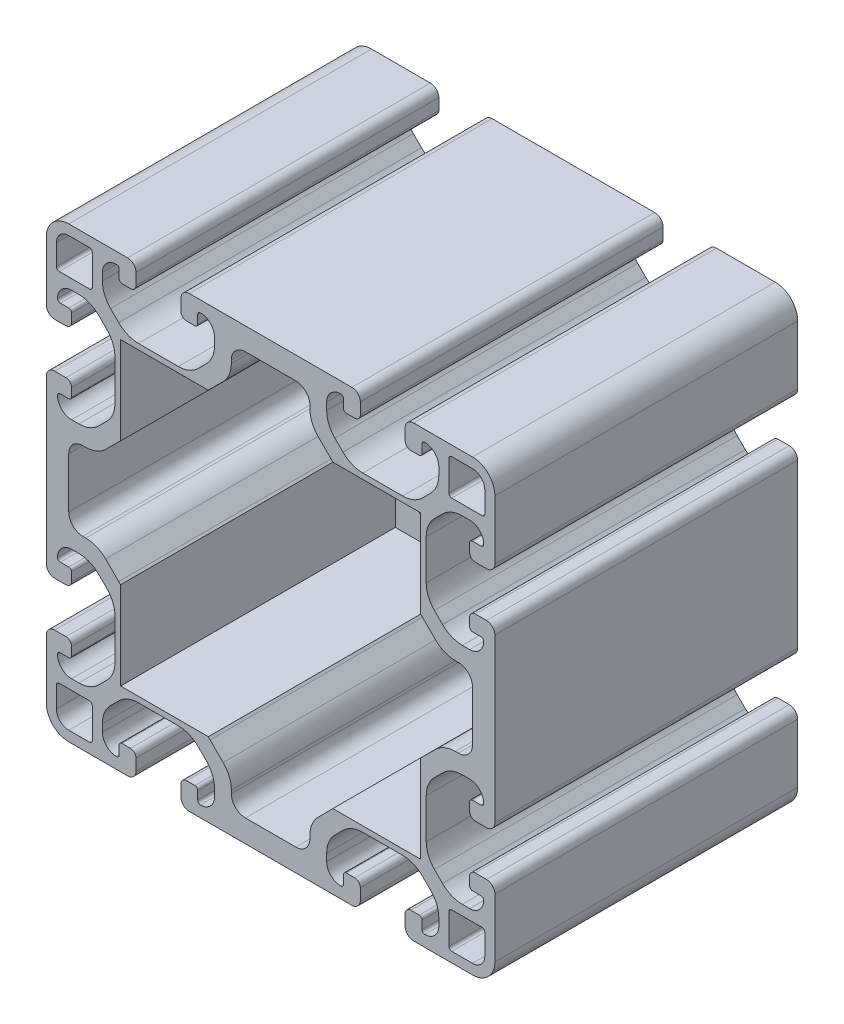
SolidWorks part; units mm, degrees
ref_plane "Plan de face" through (0, 0, 0) normal (0, 0, 1) x (1, 0, 0)
ref_plane "Plan de dessus" through (0, 0, 0) normal (0, 1, 0) x (1, 0, 0)
ref_plane "Plan de droite" through (0, 0, 0) normal (1, 0, 0) x (0, 0, -1)
ref_plane "Plan1" through (0, 0, -30) normal (0, 0, -1) x (-1, 0, 0)
sketch "Esquisse1" plane through (0, 0, -30) normal (0, 0, -1) x (-1, 0, 0)
  line L0 (-4.5, 55) -> (-4.5, 53.5)
  line L1 (-4, 53) -> (-2.5, 53)
  line L2 (-4.5, 50) -> (-5.8076, 50)
  line L3 (-9.3431, 51.4645) -> (-10.7855, 52.9069)
  line L4 (-12.25, 56.4424) -> (-12.25, 63.5576)
  line L5 (-10.7855, 67.0931) -> (-9.3431, 68.5355)
  line L6 (-5.8076, 70) -> (-4.5, 70)
  line L7 (-2.5, 67) -> (-4, 67)
  line L8 (-4.5, 66.5) -> (-4.5, 65)
  line L9 (-3.5, 64) -> (-1.5, 64)
  line L10 (0, 65.5) -> (0, 76)
  line L11 (-4, 80) -> (-14.5, 80)
  line L12 (-16, 78.5) -> (-16, 76.5)
  line L13 (-15, 75.5) -> (-13.5, 75.5)
  line L14 (-13, 76) -> (-13, 77.5)
  line L15 (-10, 75.5) -> (-10, 74.1924)
  line L16 (-11.4645, 70.6569) -> (-12.9069, 69.2145)
  line L17 (-16.4424, 67.75) -> (-23.5576, 67.75)
  line L18 (-27.0931, 69.2145) -> (-28.5355, 70.6569)
  line L19 (-30, 74.1924) -> (-30, 75.5)
  line L20 (-27, 77.5) -> (-27, 76)
  line L21 (-26.5, 75.5) -> (-25, 75.5)
  line L22 (-24, 76.5) -> (-24, 78.5)
  line L23 (-25.5, 80) -> (-54.5, 80)
  line L24 (-56, 78.5) -> (-56, 76.5)
  line L25 (-55, 75.5) -> (-53.5, 75.5)
  line L26 (-53, 76) -> (-53, 77.5)
  line L27 (-50, 75.5) -> (-50, 74.1924)
  line L28 (-51.4645, 70.6569) -> (-52.9069, 69.2145)
  line L29 (-56.4424, 67.75) -> (-63.5576, 67.75)
  line L30 (-67.0931, 69.2145) -> (-68.5355, 70.6569)
  line L31 (-70, 74.1924) -> (-70, 75.5)
  line L32 (-67, 77.5) -> (-67, 76)
  line L33 (-66.5, 75.5) -> (-65, 75.5)
  line L34 (-64, 76.5) -> (-64, 78.5)
  line L35 (-65.5, 80) -> (-76, 80)
  line L36 (-80, 76) -> (-80, 65.5)
  line L37 (-78.5, 64) -> (-76.5, 64)
  line L38 (-75.5, 65) -> (-75.5, 66.5)
  line L39 (-76, 67) -> (-77.5, 67)
  line L40 (-75.5, 70) -> (-74.1924, 70)
  line L41 (-70.6569, 68.5355) -> (-69.2145, 67.0931)
  line L42 (-67.75, 63.5576) -> (-67.75, 56.4424)
  line L43 (-69.2145, 52.9069) -> (-70.6569, 51.4645)
  line L44 (-74.1924, 50) -> (-75.5, 50)
  line L45 (-77.5, 53) -> (-76, 53)
  line L46 (-75.5, 53.5) -> (-75.5, 55)
  line L47 (-76.5, 56) -> (-78.5, 56)
  line L48 (-80, 54.5) -> (-80, 25.5)
  line L49 (-78.5, 24) -> (-76.5, 24)
  line L50 (-75.5, 25) -> (-75.5, 26.5)
  line L51 (-76, 27) -> (-77.5, 27)
  line L52 (-75.5, 30) -> (-74.1924, 30)
  line L53 (-70.6569, 28.5355) -> (-69.2145, 27.0931)
  line L54 (-67.75, 23.5576) -> (-67.75, 16.4424)
  line L55 (-69.2145, 12.9069) -> (-70.6569, 11.4645)
  line L56 (-74.1924, 10) -> (-75.5, 10)
  line L57 (-77.5, 13) -> (-76, 13)
  line L58 (-75.5, 13.5) -> (-75.5, 15)
  line L59 (-76.5, 16) -> (-78.5, 16)
  line L60 (-80, 14.5) -> (-80, 4)
  line L61 (-76, 0) -> (-65.5, 0)
  line L62 (-64, 1.5) -> (-64, 3.5)
  line L63 (-65, 4.5) -> (-66.5, 4.5)
  line L64 (-67, 4) -> (-67, 2.5)
  line L65 (-70, 4.5) -> (-70, 5.8076)
  line L66 (-68.5355, 9.3431) -> (-67.0931, 10.7855)
  line L67 (-63.5576, 12.25) -> (-56.4424, 12.25)
  line L68 (-52.9069, 10.7855) -> (-51.4645, 9.3431)
  line L69 (-50, 5.8076) -> (-50, 4.5)
  line L70 (-53, 2.5) -> (-53, 4)
  line L71 (-53.5, 4.5) -> (-55, 4.5)
  line L72 (-56, 3.5) -> (-56, 1.5)
  line L73 (-54.5, 0) -> (-25.5, 0)
  line L74 (-24, 1.5) -> (-24, 3.5)
  line L75 (-25, 4.5) -> (-26.5, 4.5)
  line L76 (-27, 4) -> (-27, 2.5)
  line L77 (-30, 4.5) -> (-30, 5.8076)
  line L78 (-28.5355, 9.3431) -> (-27.0931, 10.7855)
  line L79 (-23.5576, 12.25) -> (-16.4424, 12.25)
  line L80 (-12.9069, 10.7855) -> (-11.4645, 9.3431)
  line L81 (-10, 5.8076) -> (-10, 4.5)
  line L82 (-13, 2.5) -> (-13, 4)
  line L83 (-13.5, 4.5) -> (-15, 4.5)
  line L84 (-16, 3.5) -> (-16, 1.5)
  line L85 (-14.5, 0) -> (-4, 0)
  line L86 (0, 4) -> (0, 14.5)
  line L87 (-1.5, 16) -> (-3.5, 16)
  line L88 (-4.5, 15) -> (-4.5, 13.5)
  line L89 (-4, 13) -> (-2.5, 13)
  line L90 (-4.5, 10) -> (-5.8076, 10)
  line L91 (-9.3431, 11.4645) -> (-10.7855, 12.9069)
  line L92 (-12.25, 16.4424) -> (-12.25, 23.5576)
  line L93 (-10.7855, 27.0931) -> (-9.3431, 28.5355)
  line L94 (-5.8076, 30) -> (-4.5, 30)
  line L95 (-2.5, 27) -> (-4, 27)
  line L96 (-4.5, 26.5) -> (-4.5, 25)
  line L97 (-3.5, 24) -> (-1.5, 24)
  line L98 (0, 25.5) -> (0, 54.5)
  line L99 (-1.5, 56) -> (-3.5, 56)
  line L100 (-24.1122, 27.6036) -> (-27.6036, 24.1122)
  line L101 (-27.75, 23.7586) -> (-27.75, 16.4424)
  line L102 (-29.2145, 12.9069) -> (-31.5355, 10.5858)
  line L103 (-33, 7.0503) -> (-33, 6.5)
  line L104 (-35.5, 4) -> (-44.5, 4)
  line L105 (-47, 6.5) -> (-47, 7.0503)
  line L106 (-48.4645, 10.5858) -> (-50.7855, 12.9069)
  line L107 (-52.25, 16.4424) -> (-52.25, 23.7586)
  line L108 (-52.3964, 24.1122) -> (-55.8878, 27.6036)
  line L109 (-56.2414, 27.75) -> (-63.5576, 27.75)
  line L110 (-67.0931, 29.2145) -> (-69.4142, 31.5355)
  line L111 (-72.9497, 33) -> (-73.5, 33)
  line L112 (-76, 35.5) -> (-76, 44.5)
  line L113 (-73.5, 47) -> (-72.9497, 47)
  line L114 (-69.4142, 48.4645) -> (-67.0931, 50.7855)
  line L115 (-63.5576, 52.25) -> (-56.2414, 52.25)
  line L116 (-55.8878, 52.3964) -> (-52.3964, 55.8878)
  line L117 (-52.25, 56.2414) -> (-52.25, 63.5576)
  line L118 (-50.7855, 67.0931) -> (-48.4645, 69.4142)
  line L119 (-47, 72.9497) -> (-47, 73.5)
  line L120 (-44.5, 76) -> (-35.5, 76)
  line L121 (-33, 73.5) -> (-33, 72.9497)
  line L122 (-31.5355, 69.4142) -> (-29.2145, 67.0931)
  line L123 (-27.75, 63.5576) -> (-27.75, 56.2414)
  line L124 (-27.6036, 55.8878) -> (-24.1122, 52.3964)
  line L125 (-23.7586, 52.25) -> (-16.4424, 52.25)
  line L126 (-12.9069, 50.7855) -> (-10.5858, 48.4645)
  line L127 (-7.0503, 47) -> (-6.5, 47)
  line L128 (-4, 44.5) -> (-4, 35.5)
  line L129 (-6.5, 33) -> (-7.0503, 33)
  line L130 (-10.5858, 31.5355) -> (-12.9069, 29.2145)
  line L131 (-16.4424, 27.75) -> (-23.7586, 27.75)
  line L132 (-4, 1.8) -> (-7.7, 1.8)
  line L133 (-8.2, 2.3) -> (-8.2, 7.7)
  line L134 (-7.7, 8.2) -> (-2.3, 8.2)
  line L135 (-1.8, 7.7) -> (-1.8, 4)
  line L136 (-78.2, 4) -> (-78.2, 7.7)
  line L137 (-77.7, 8.2) -> (-72.3, 8.2)
  line L138 (-71.8, 7.7) -> (-71.8, 2.3)
  line L139 (-72.3, 1.8) -> (-76, 1.8)
  line L140 (-76, 78.2) -> (-72.3, 78.2)
  line L141 (-71.8, 77.7) -> (-71.8, 72.3)
  line L142 (-72.3, 71.8) -> (-77.7, 71.8)
  line L143 (-78.2, 72.3) -> (-78.2, 76)
  line L144 (-1.8, 76) -> (-1.8, 72.3)
  line L145 (-2.3, 71.8) -> (-7.7, 71.8)
  line L146 (-8.2, 72.3) -> (-8.2, 77.7)
  line L147 (-7.7, 78.2) -> (-4, 78.2)
  arc A0 (-4.5, 53.5) -> (-4, 53) centre (-4, 53.5) ccw
  arc A1 (-2.5, 53) -> (-2, 52.5) centre (-2.5, 52.5) cw
  arc A2 (-2, 52.5) -> (-4.5, 50) centre (-4.5, 52.5) cw
  arc A3 (-5.8076, 50) -> (-9.3431, 51.4645) centre (-5.8076, 55) cw
  arc A4 (-10.7855, 52.9069) -> (-12.25, 56.4424) centre (-7.25, 56.4424) cw
  arc A5 (-12.25, 63.5576) -> (-10.7855, 67.0931) centre (-7.25, 63.5576) cw
  arc A6 (-9.3431, 68.5355) -> (-5.8076, 70) centre (-5.8076, 65) cw
  arc A7 (-4.5, 70) -> (-2, 67.5) centre (-4.5, 67.5) cw
  arc A8 (-2, 67.5) -> (-2.5, 67) centre (-2.5, 67.5) cw
  arc A9 (-4, 67) -> (-4.5, 66.5) centre (-4, 66.5) ccw
  arc A10 (-4.5, 65) -> (-3.5, 64) centre (-3.5, 65) ccw
  arc A11 (-1.5, 64) -> (0, 65.5) centre (-1.5, 65.5) ccw
  arc A12 (0, 76) -> (-4, 80) centre (-4, 76) ccw
  arc A13 (-14.5, 80) -> (-16, 78.5) centre (-14.5, 78.5) ccw
  arc A14 (-16, 76.5) -> (-15, 75.5) centre (-15, 76.5) ccw
  arc A15 (-13.5, 75.5) -> (-13, 76) centre (-13.5, 76) ccw
  arc A16 (-13, 77.5) -> (-12.5, 78) centre (-12.5, 77.5) cw
  arc A17 (-12.5, 78) -> (-10, 75.5) centre (-12.5, 75.5) cw
  arc A18 (-10, 74.1924) -> (-11.4645, 70.6569) centre (-15, 74.1924) cw
  arc A19 (-12.9069, 69.2145) -> (-16.4424, 67.75) centre (-16.4424, 72.75) cw
  arc A20 (-23.5576, 67.75) -> (-27.0931, 69.2145) centre (-23.5576, 72.75) cw
  arc A21 (-28.5355, 70.6569) -> (-30, 74.1924) centre (-25, 74.1924) cw
  arc A22 (-30, 75.5) -> (-27.5, 78) centre (-27.5, 75.5) cw
  arc A23 (-27.5, 78) -> (-27, 77.5) centre (-27.5, 77.5) cw
  arc A24 (-27, 76) -> (-26.5, 75.5) centre (-26.5, 76) ccw
  arc A25 (-25, 75.5) -> (-24, 76.5) centre (-25, 76.5) ccw
  arc A26 (-24, 78.5) -> (-25.5, 80) centre (-25.5, 78.5) ccw
  arc A27 (-54.5, 80) -> (-56, 78.5) centre (-54.5, 78.5) ccw
  arc A28 (-56, 76.5) -> (-55, 75.5) centre (-55, 76.5) ccw
  arc A29 (-53.5, 75.5) -> (-53, 76) centre (-53.5, 76) ccw
  arc A30 (-53, 77.5) -> (-52.5, 78) centre (-52.5, 77.5) cw
  arc A31 (-52.5, 78) -> (-50, 75.5) centre (-52.5, 75.5) cw
  arc A32 (-50, 74.1924) -> (-51.4645, 70.6569) centre (-55, 74.1924) cw
  arc A33 (-52.9069, 69.2145) -> (-56.4424, 67.75) centre (-56.4424, 72.75) cw
  arc A34 (-63.5576, 67.75) -> (-67.0931, 69.2145) centre (-63.5576, 72.75) cw
  arc A35 (-68.5355, 70.6569) -> (-70, 74.1924) centre (-65, 74.1924) cw
  arc A36 (-70, 75.5) -> (-67.5, 78) centre (-67.5, 75.5) cw
  arc A37 (-67.5, 78) -> (-67, 77.5) centre (-67.5, 77.5) cw
  arc A38 (-67, 76) -> (-66.5, 75.5) centre (-66.5, 76) ccw
  arc A39 (-65, 75.5) -> (-64, 76.5) centre (-65, 76.5) ccw
  arc A40 (-64, 78.5) -> (-65.5, 80) centre (-65.5, 78.5) ccw
  arc A41 (-76, 80) -> (-80, 76) centre (-76, 76) ccw
  arc A42 (-80, 65.5) -> (-78.5, 64) centre (-78.5, 65.5) ccw
  arc A43 (-76.5, 64) -> (-75.5, 65) centre (-76.5, 65) ccw
  arc A44 (-75.5, 66.5) -> (-76, 67) centre (-76, 66.5) ccw
  arc A45 (-77.5, 67) -> (-78, 67.5) centre (-77.5, 67.5) cw
  arc A46 (-78, 67.5) -> (-75.5, 70) centre (-75.5, 67.5) cw
  arc A47 (-74.1924, 70) -> (-70.6569, 68.5355) centre (-74.1924, 65) cw
  arc A48 (-69.2145, 67.0931) -> (-67.75, 63.5576) centre (-72.75, 63.5576) cw
  arc A49 (-67.75, 56.4424) -> (-69.2145, 52.9069) centre (-72.75, 56.4424) cw
  arc A50 (-70.6569, 51.4645) -> (-74.1924, 50) centre (-74.1924, 55) cw
  arc A51 (-75.5, 50) -> (-78, 52.5) centre (-75.5, 52.5) cw
  arc A52 (-78, 52.5) -> (-77.5, 53) centre (-77.5, 52.5) cw
  arc A53 (-76, 53) -> (-75.5, 53.5) centre (-76, 53.5) ccw
  arc A54 (-75.5, 55) -> (-76.5, 56) centre (-76.5, 55) ccw
  arc A55 (-78.5, 56) -> (-80, 54.5) centre (-78.5, 54.5) ccw
  arc A56 (-80, 25.5) -> (-78.5, 24) centre (-78.5, 25.5) ccw
  arc A57 (-76.5, 24) -> (-75.5, 25) centre (-76.5, 25) ccw
  arc A58 (-75.5, 26.5) -> (-76, 27) centre (-76, 26.5) ccw
  arc A59 (-77.5, 27) -> (-78, 27.5) centre (-77.5, 27.5) cw
  arc A60 (-78, 27.5) -> (-75.5, 30) centre (-75.5, 27.5) cw
  arc A61 (-74.1924, 30) -> (-70.6569, 28.5355) centre (-74.1924, 25) cw
  arc A62 (-69.2145, 27.0931) -> (-67.75, 23.5576) centre (-72.75, 23.5576) cw
  arc A63 (-67.75, 16.4424) -> (-69.2145, 12.9069) centre (-72.75, 16.4424) cw
  arc A64 (-70.6569, 11.4645) -> (-74.1924, 10) centre (-74.1924, 15) cw
  arc A65 (-75.5, 10) -> (-78, 12.5) centre (-75.5, 12.5) cw
  arc A66 (-78, 12.5) -> (-77.5, 13) centre (-77.5, 12.5) cw
  arc A67 (-76, 13) -> (-75.5, 13.5) centre (-76, 13.5) ccw
  arc A68 (-75.5, 15) -> (-76.5, 16) centre (-76.5, 15) ccw
  arc A69 (-78.5, 16) -> (-80, 14.5) centre (-78.5, 14.5) ccw
  arc A70 (-80, 4) -> (-76, 0) centre (-76, 4) ccw
  arc A71 (-65.5, 0) -> (-64, 1.5) centre (-65.5, 1.5) ccw
  arc A72 (-64, 3.5) -> (-65, 4.5) centre (-65, 3.5) ccw
  arc A73 (-66.5, 4.5) -> (-67, 4) centre (-66.5, 4) ccw
  arc A74 (-67, 2.5) -> (-67.5, 2) centre (-67.5, 2.5) cw
  arc A75 (-67.5, 2) -> (-70, 4.5) centre (-67.5, 4.5) cw
  arc A76 (-70, 5.8076) -> (-68.5355, 9.3431) centre (-65, 5.8076) cw
  arc A77 (-67.0931, 10.7855) -> (-63.5576, 12.25) centre (-63.5576, 7.25) cw
  arc A78 (-56.4424, 12.25) -> (-52.9069, 10.7855) centre (-56.4424, 7.25) cw
  arc A79 (-51.4645, 9.3431) -> (-50, 5.8076) centre (-55, 5.8076) cw
  arc A80 (-50, 4.5) -> (-52.5, 2) centre (-52.5, 4.5) cw
  arc A81 (-52.5, 2) -> (-53, 2.5) centre (-52.5, 2.5) cw
  arc A82 (-53, 4) -> (-53.5, 4.5) centre (-53.5, 4) ccw
  arc A83 (-55, 4.5) -> (-56, 3.5) centre (-55, 3.5) ccw
  arc A84 (-56, 1.5) -> (-54.5, 0) centre (-54.5, 1.5) ccw
  arc A85 (-25.5, 0) -> (-24, 1.5) centre (-25.5, 1.5) ccw
  arc A86 (-24, 3.5) -> (-25, 4.5) centre (-25, 3.5) ccw
  arc A87 (-26.5, 4.5) -> (-27, 4) centre (-26.5, 4) ccw
  arc A88 (-27, 2.5) -> (-27.5, 2) centre (-27.5, 2.5) cw
  arc A89 (-27.5, 2) -> (-30, 4.5) centre (-27.5, 4.5) cw
  arc A90 (-30, 5.8076) -> (-28.5355, 9.3431) centre (-25, 5.8076) cw
  arc A91 (-27.0931, 10.7855) -> (-23.5576, 12.25) centre (-23.5576, 7.25) cw
  arc A92 (-16.4424, 12.25) -> (-12.9069, 10.7855) centre (-16.4424, 7.25) cw
  arc A93 (-11.4645, 9.3431) -> (-10, 5.8076) centre (-15, 5.8076) cw
  arc A94 (-10, 4.5) -> (-12.5, 2) centre (-12.5, 4.5) cw
  arc A95 (-12.5, 2) -> (-13, 2.5) centre (-12.5, 2.5) cw
  arc A96 (-13, 4) -> (-13.5, 4.5) centre (-13.5, 4) ccw
  arc A97 (-15, 4.5) -> (-16, 3.5) centre (-15, 3.5) ccw
  arc A98 (-16, 1.5) -> (-14.5, 0) centre (-14.5, 1.5) ccw
  arc A99 (-4, 0) -> (0, 4) centre (-4, 4) ccw
  arc A100 (0, 14.5) -> (-1.5, 16) centre (-1.5, 14.5) ccw
  arc A101 (-3.5, 16) -> (-4.5, 15) centre (-3.5, 15) ccw
  arc A102 (-4.5, 13.5) -> (-4, 13) centre (-4, 13.5) ccw
  arc A103 (-2.5, 13) -> (-2, 12.5) centre (-2.5, 12.5) cw
  arc A104 (-2, 12.5) -> (-4.5, 10) centre (-4.5, 12.5) cw
  arc A105 (-5.8076, 10) -> (-9.3431, 11.4645) centre (-5.8076, 15) cw
  arc A106 (-10.7855, 12.9069) -> (-12.25, 16.4424) centre (-7.25, 16.4424) cw
  arc A107 (-12.25, 23.5576) -> (-10.7855, 27.0931) centre (-7.25, 23.5576) cw
  arc A108 (-9.3431, 28.5355) -> (-5.8076, 30) centre (-5.8076, 25) cw
  arc A109 (-4.5, 30) -> (-2, 27.5) centre (-4.5, 27.5) cw
  arc A110 (-2, 27.5) -> (-2.5, 27) centre (-2.5, 27.5) cw
  arc A111 (-4, 27) -> (-4.5, 26.5) centre (-4, 26.5) ccw
  arc A112 (-4.5, 25) -> (-3.5, 24) centre (-3.5, 25) ccw
  arc A113 (-1.5, 24) -> (0, 25.5) centre (-1.5, 25.5) ccw
  arc A114 (0, 54.5) -> (-1.5, 56) centre (-1.5, 54.5) ccw
  arc A115 (-3.5, 56) -> (-4.5, 55) centre (-3.5, 55) ccw
  circle A116 centre (-20, 20) radius 3.4
  circle A117 centre (-20, 60) radius 3.4
  circle A118 centre (-60, 20) radius 3.4
  circle A119 centre (-60, 60) radius 3.4
  arc A120 (-23.7586, 27.75) -> (-24.1122, 27.6036) centre (-23.7586, 27.25) ccw
  arc A121 (-27.6036, 24.1122) -> (-27.75, 23.7586) centre (-27.25, 23.7586) ccw
  arc A122 (-27.75, 16.4424) -> (-29.2145, 12.9069) centre (-32.75, 16.4424) cw
  arc A123 (-31.5355, 10.5858) -> (-33, 7.0503) centre (-28, 7.0503) ccw
  arc A124 (-33, 6.5) -> (-35.5, 4) centre (-35.5, 6.5) cw
  arc A125 (-44.5, 4) -> (-47, 6.5) centre (-44.5, 6.5) cw
  arc A126 (-47, 7.0503) -> (-48.4645, 10.5858) centre (-52, 7.0503) ccw
  arc A127 (-50.7855, 12.9069) -> (-52.25, 16.4424) centre (-47.25, 16.4424) cw
  arc A128 (-52.25, 23.7586) -> (-52.3964, 24.1122) centre (-52.75, 23.7586) ccw
  arc A129 (-55.8878, 27.6036) -> (-56.2414, 27.75) centre (-56.2414, 27.25) ccw
  arc A130 (-63.5576, 27.75) -> (-67.0931, 29.2145) centre (-63.5576, 32.75) cw
  arc A131 (-69.4142, 31.5355) -> (-72.9497, 33) centre (-72.9497, 28) ccw
  arc A132 (-73.5, 33) -> (-76, 35.5) centre (-73.5, 35.5) cw
  arc A133 (-76, 44.5) -> (-73.5, 47) centre (-73.5, 44.5) cw
  arc A134 (-72.9497, 47) -> (-69.4142, 48.4645) centre (-72.9497, 52) ccw
  arc A135 (-67.0931, 50.7855) -> (-63.5576, 52.25) centre (-63.5576, 47.25) cw
  arc A136 (-56.2414, 52.25) -> (-55.8878, 52.3964) centre (-56.2414, 52.75) ccw
  arc A137 (-52.3964, 55.8878) -> (-52.25, 56.2414) centre (-52.75, 56.2414) ccw
  arc A138 (-52.25, 63.5576) -> (-50.7855, 67.0931) centre (-47.25, 63.5576) cw
  arc A139 (-48.4645, 69.4142) -> (-47, 72.9497) centre (-52, 72.9497) ccw
  arc A140 (-47, 73.5) -> (-44.5, 76) centre (-44.5, 73.5) cw
  arc A141 (-35.5, 76) -> (-33, 73.5) centre (-35.5, 73.5) cw
  arc A142 (-33, 72.9497) -> (-31.5355, 69.4142) centre (-28, 72.9497) ccw
  arc A143 (-29.2145, 67.0931) -> (-27.75, 63.5576) centre (-32.75, 63.5576) cw
  arc A144 (-27.75, 56.2414) -> (-27.6036, 55.8878) centre (-27.25, 56.2414) ccw
  arc A145 (-24.1122, 52.3964) -> (-23.7586, 52.25) centre (-23.7586, 52.75) ccw
  arc A146 (-16.4424, 52.25) -> (-12.9069, 50.7855) centre (-16.4424, 47.25) cw
  arc A147 (-10.5858, 48.4645) -> (-7.0503, 47) centre (-7.0503, 52) ccw
  arc A148 (-6.5, 47) -> (-4, 44.5) centre (-6.5, 44.5) cw
  arc A149 (-4, 35.5) -> (-6.5, 33) centre (-6.5027, 35.5027) cw
  arc A150 (-7.0503, 33) -> (-10.5858, 31.5355) centre (-7.0503, 28) ccw
  arc A151 (-12.9069, 29.2145) -> (-16.4424, 27.75) centre (-16.4424, 32.75) cw
  arc A152 (-1.8, 4) -> (-4, 1.8) centre (-4, 4) cw
  arc A153 (-7.7, 1.8) -> (-8.2, 2.3) centre (-7.7, 2.3) cw
  arc A154 (-8.2, 7.7) -> (-7.7, 8.2) centre (-7.7, 7.7) cw
  arc A155 (-2.3, 8.2) -> (-1.8, 7.7) centre (-2.3, 7.7) cw
  arc A156 (-76, 1.8) -> (-78.2, 4) centre (-76, 4) cw
  arc A157 (-78.2, 7.7) -> (-77.7, 8.2) centre (-77.7, 7.7) cw
  arc A158 (-72.3, 8.2) -> (-71.8, 7.7) centre (-72.3, 7.7) cw
  arc A159 (-71.8, 2.3) -> (-72.3, 1.8) centre (-72.3, 2.3) cw
  arc A160 (-78.2, 76) -> (-76, 78.2) centre (-76, 76) cw
  arc A161 (-72.3, 78.2) -> (-71.8, 77.7) centre (-72.3, 77.7) cw
  arc A162 (-71.8, 72.3) -> (-72.3, 71.8) centre (-72.3, 72.3) cw
  arc A163 (-77.7, 71.8) -> (-78.2, 72.3) centre (-77.7, 72.3) cw
  arc A164 (-4, 78.2) -> (-1.8, 76) centre (-4, 76) cw
  arc A165 (-1.8, 72.3) -> (-2.3, 71.8) centre (-2.3, 72.3) cw
  arc A166 (-7.7, 71.8) -> (-8.2, 72.3) centre (-7.7, 72.3) cw
  arc A167 (-8.2, 77.7) -> (-7.7, 78.2) centre (-7.7, 77.7) cw
extrude "Boss.-Extru.1" add sketch "Esquisse1" against normal blind 54
sketch "Esquisse2" plane through (0, 0, 24) normal (0, 0, 1) x (1, 0, 0)
  line L0 (4, 40) -> (76, 40) construction
  line L1 (4, 35.5) -> (4, 44.5) construction
  line L2 (76, 44.5) -> (76, 35.5) construction
  line L3 (40, 76) -> (40, -2.6712) construction
  line L4 (35.5, 76) -> (44.5, 76) construction
  line L5 (12.25, 56.4424) -> (12.25, 63.5576) construction
  line L6 (13.25, 13.25) -> (66.75, 13.25)
  line L7 (13.25, 13.25) -> (13.25, 66.75)
  line L8 (13.25, 66.75) -> (66.75, 66.75)
  line L9 (66.75, 13.25) -> (66.75, 66.75)
  line L10 (13.25, 13.25) -> (66.75, 66.75) construction
  line L11 (13.25, 66.75) -> (66.75, 13.25) construction
  line L12 (16.4424, 67.75) -> (23.5576, 67.75) construction
  point P10 (40, 40)
  dimension "D1" = 1
  dimension "D2" = 1
extrude "Enlèv. mat.-Extru.1" cut sketch "Esquisse2" against normal blind 49
